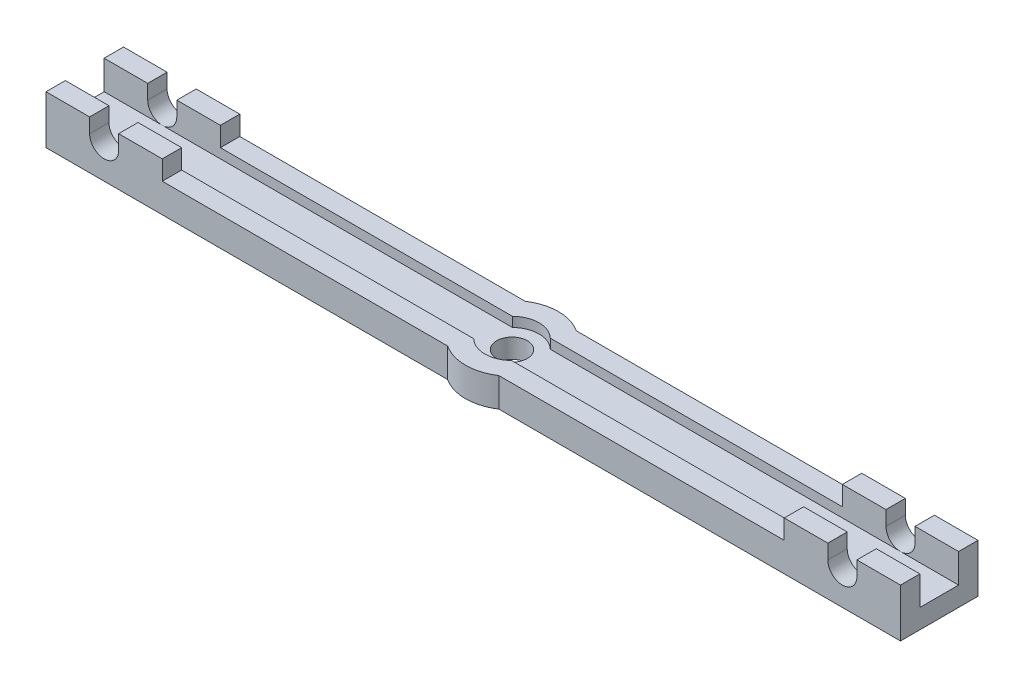
SolidWorks part; units mm, degrees
ref_plane "Front Plane" through (0, 0, 0) normal (0, 0, 1) x (1, 0, 0)
ref_plane "Top Plane" through (0, 0, 0) normal (0, 1, 0) x (1, 0, 0)
ref_plane "Right Plane" through (0, 0, 0) normal (1, 0, 0) x (0, 0, -1)
sketch "Sketch1" plane through (0, 0, 0) normal (0, 1, 0) x (1, 0, 0)
  line L1 (0, -4) -> (44.1, -4)
  line L2 (0, -4) -> (0, 4)
  line L3 (0, 4) -> (44.1, 4)
  line L4 (44.1, -4) -> (44.1, 4)
  point P4 (0, 0)
  dimension "D1" = 44.1
  dimension "D2" = 8
extrude "Boss-Extrude1" add sketch "Sketch1" along normal blind 2
sketch "Sketch2" plane through (0, 2, 0) normal (0, 1, 0) x (1, 0, 0)
  line L1 (44.1, 4) -> (32.1, 4)
  line L2 (44.1, 4) -> (44.1, 2)
  line L3 (44.1, 2) -> (32.1, 2)
  line L4 (32.1, 4) -> (32.1, 2)
  line L5 (44.1, -4) -> (32.1, -4)
  line L6 (44.1, -4) -> (44.1, -2)
  line L7 (44.1, -2) -> (32.1, -2)
  line L8 (32.1, -4) -> (32.1, -2)
  dimension "D1" = 2
  dimension "D2" = 12
extrude "Boss-Extrude2" add sketch "Sketch2" along normal blind 3
sketch "Sketch3" plane through (0, 0, 4) normal (0, 0, 1) x (1, 0, 0)
  line L0 (44.1, 5) -> (44.1, 0) construction
  line L1 (32.1, 5) -> (44.1, 5) construction
  line L2 (36.6, 3.5) -> (36.6, 5)
  line L3 (36.6, 5) -> (39.6, 5)
  line L4 (39.6, 5) -> (39.6, 3.5)
  arc A0 (36.6, 3.5) -> (39.6, 3.5) centre (38.1, 3.5) ccw
  dimension "D1" = 3
  dimension "D2" = 6
  dimension "D3" = 1.5
extrude "Cut-Extrude1" cut sketch "Sketch3" against normal through all
sketch "Sketch4" plane through (0, 2, 0) normal (0, 1, 0) x (1, 0, 0)
  line L0 (0, 4) -> (0, -4) construction
  line L1 (32.1, -4) -> (0, -4)
  line L2 (32.1, -4) -> (32.1, -2)
  line L3 (32.1, -2) -> (0, -2)
  line L4 (0, -4) -> (0, -2)
  line L6 (32.1, 2) -> (0, 2)
  line L7 (32.1, 2) -> (32.1, 4)
  line L8 (32.1, 4) -> (0, 4)
  line L9 (0, 2) -> (0, 4)
extrude "Boss-Extrude3" add sketch "Sketch4" along normal blind 1
mirror "Mirror1" about plane through (0, 0, 0) normal (1, 0, 0) of "Boss-Extrude3", "Cut-Extrude1", "Boss-Extrude2", "Boss-Extrude1"
sketch "Sketch7" plane through (0, 2, 0) normal (0, 1, 0) x (1, 0, 0)
  circle A0 centre (0, 0) radius 2.794
  dimension "D1" = 5.588
extrude "Cut-Extrude3" cut sketch "Sketch7" along normal through all
sketch "Sketch8" plane through (0, 2, 0) normal (0, 1, 0) x (1, 0, 0)
  circle A0 centre (0, 0) radius 1.5875
  dimension "D1" = 3.175
extrude "Cut-Extrude4" cut sketch "Sketch8" against normal through all
sketch "Sketch9" plane through (0, 3, 0) normal (0, 1, 0) x (1, 0, 0)
  line L0 (-32.1, -4) -> (32.1, -4) construction
  line L1 (32.1, 4) -> (-32.1, 4) construction
  line L2 (-2.6424, -4) -> (2.6424, -4)
  line L3 (2.6424, 4) -> (-2.6424, 4)
  arc A8 (-2.6424, -4) -> (2.6424, -4) centre (0, 0) ccw
  arc A9 (1.951, 2) -> (-1.951, 2) centre (0, 0) ccw construction
  arc A10 (2.6424, 4) -> (-2.6424, 4) centre (0, 0) ccw
  dimension "D1" = 2
extrude "Boss-Extrude4" add sketch "Sketch9" against normal up to surface (3 mm away) up to face at (0, 0, 1.5875)
